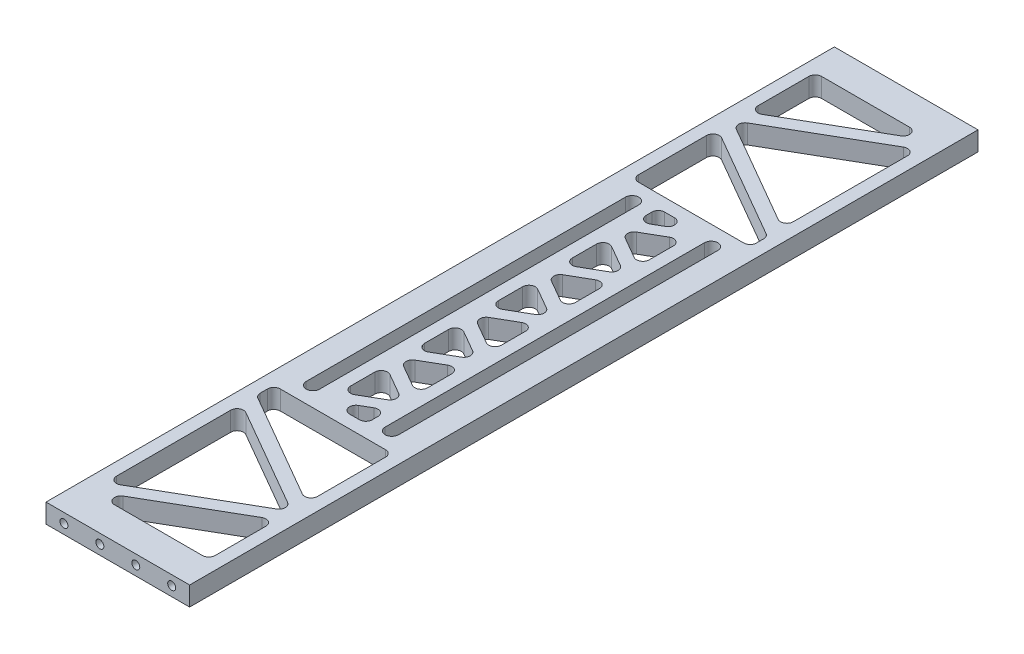
SolidWorks part; units mm, degrees
material "Сплав 2024"
ref_plane "Спереди" through (0, 0, 0) normal (0, 0, 1) x (1, 0, 0)
ref_plane "Сверху" through (0, 0, 0) normal (0, 1, 0) x (1, 0, 0)
ref_plane "Справа" through (0, 0, 0) normal (1, 0, 0) x (0, 0, -1)
sketch "Эскиз1" plane through (0, 0, 0) normal (0, 1, 0) x (1, 0, 0)
  line L2 (-15.9099, 15.9099) -> (15.9099, -15.9099) construction
  line L3 (15.9099, 15.9099) -> (-15.9099, -15.9099) construction
  line L4 (-22.5, 0) -> (-22.5, -247)
  line L5 (-22.5, -247) -> (22.5, -247)
  line L6 (22.5, 0) -> (22.5, -247)
  line L7 (-22.5, 0) -> (22.5, 0)
  dimension "D1" = 247
  dimension "D2" = 45
  dimension "D3" = 45
extrude "Бобышка-Вытянуть1" add sketch "Эскиз1" along normal blind 6
sketch "Эскиз2" plane through (0, 6, 0) normal (0, 1, 0) x (1, 0, 0)
  line L2 (0, 0) -> (0, -247) construction
  line L3 (-22.5, -247) -> (22.5, -247) construction
  line L4 (-12.3744, -135.8744) -> (12.3744, -111.1256) construction
  line L5 (-12.3744, -73.5) -> (-12.3744, -173.5) construction
  line L6 (-10.2744, -73.5) -> (-10.2744, -173.5)
  line L7 (-14.4744, -73.5) -> (-14.4744, -173.5)
  line L8 (-12.3744, -111.1256) -> (12.3744, -135.8744) construction
  line L9 (12.3744, -73.5) -> (12.3744, -173.5) construction
  line L10 (10.2744, -73.5) -> (10.2744, -173.5)
  line L11 (14.4744, -73.5) -> (14.4744, -173.5)
  line L13 (-22.5, -123.5) -> (22.5, -123.5) construction
  line L14 (-22.5, 0) -> (-22.5, -247) construction
  line L15 (22.5, -247) -> (22.5, 0) construction
  circle A0 centre (0, -123.5) radius 6 construction
  circle A1 centre (0, -123.5) radius 17.5 construction
  arc A2 (-10.2744, -73.5) -> (-14.4744, -73.5) centre (-12.3744, -73.5) ccw
  arc A3 (-14.4744, -173.5) -> (-10.2744, -173.5) centre (-12.3744, -173.5) ccw
  arc A4 (10.2744, -73.5) -> (14.4744, -73.5) centre (12.3744, -73.5) cw
  arc A5 (14.4744, -173.5) -> (10.2744, -173.5) centre (12.3744, -173.5) cw
  point P13 (12.3744, -123.5)
  point P18 (-12.3744, -123.5)
  point P37 (0, -123.5)
  dimension "D1" = 12
  dimension "D2" = 35
  dimension "D4" = 2.1
  dimension "D3" = 45
  dimension "D5" = 100
hole_wizard "Цековка для  винта с полукруглой головкой M31" [suppressed] positions "Эскиз4" profile "Эскиз5" counterbore size "M3" standard "Ansi Metric"
sketch "Эскиз4" plane through (0, 6, 0) normal (0, 1, 0) x (1, 0, 0)
  line L2 (-36.6046, 36.6046) -> (36.6046, -36.6046) construction
  line L3 (-12.3744, -12.3744) -> (12.3744, 12.3744) construction
  circle A0 centre (0, 0) radius 6 construction
  point P0 (-4.2426, 4.2426)
  point P6 (-4.2426, -4.2426)
  point P10 (4.2426, -4.2426)
  point P12 (4.2426, 4.2426)
sketch "Эскиз5" plane through (-4.2426, 6, -4.2426) normal (1, 0, 0) x (0, 0, 1)
  line L0 (0, 0) -> (0, 6)
  line L1 (0, 6) -> (1.7, 6)
  line L3 (1.7, 6) -> (1.7, 2)
  line L4 (1.7, 2) -> (3.35, 2)
  line L5 (3.35, 2) -> (3.35, 0)
  line L7 (3.35, 0) -> (0, 0)
  line L11 (0, -6.35) -> (0, 107.95) construction
  dimension "Диаметр сквозного отверстия" = 3.4
  dimension "Глубина сквозного отверстия" = 6
  dimension "Диаметр цековки" = 6.7
  dimension "Глубина цековки" = 2
hole_wizard "Отверстие обработанное метчиком M4x0.71" [suppressed] positions "Эскиз7" profile "Эскиз6" tap size "M4x0.7" standard "Ansi Metric"
sketch "Эскиз7" [suppressed] plane through (0, 4, 0) normal (0, 1, 0) x (1, 0, 0)
  line L0 (22.5, 0) -> (-22.5, 0) construction
  line L1 (0, 22.5) -> (0, -22.5) construction
  circle A0 centre (0, 0) radius 19.25 construction
  point P0 (-19.25, 0)
  point P6 (0, -19.25)
  point P10 (19.25, 0)
  point P12 (0, 19.25)
sketch "Эскиз6" plane through (-19.25, 4, 0) normal (1, 0, 0) x (0, 0, 1)
  line L0 (0, 0) -> (0, 4)
  line L1 (0, 4) -> (1.65, 4)
  line L2 (1.65, 4) -> (1.65, 0)
  line L5 (1.65, 0) -> (0, 0)
  line L11 (0, -6.35) -> (0, 107.95) construction
  dimension "Диаметр резьбы" = 3.3
  dimension "Глубина проходного сверла" = 4
extrude "Вырез-Вытянуть1" cut sketch "Эскиз2" against normal through all
sketch "Эскиз8" plane through (0, 0, 247) normal (0, 0, 1) x (1, 0, 0)
  line L0 (-22.5, 3) -> (22.5, 3) construction
  line L1 (-22.5, 6) -> (-22.5, 0) construction
  line L2 (22.5, 6) -> (22.5, 0) construction
  line L3 (-16.875, 6) -> (-16.875, 0) construction
  line L4 (-22.5, 6) -> (22.5, 6) construction
  line L5 (-22.5, 0) -> (22.5, 0) construction
  line L6 (-11.25, 6) -> (-11.25, 0) construction
  line L7 (-5.625, 6) -> (-5.625, 0) construction
  line L8 (0, 6) -> (0, 0) construction
  line L9 (5.625, 6) -> (5.625, 0) construction
  line L10 (11.25, 0) -> (11.25, 6) construction
  line L11 (16.875, 6) -> (16.875, 0) construction
  dimension "D1" = 45
  dimension "D2" = 5.625
  dimension "D3" = 5.625
  dimension "D4" = 5.625
  dimension "D5" = 5.625
  dimension "D6" = 5.625
  dimension "D7" = 5.625
  dimension "D8" = 5.625
sketch "Эскиз14" plane through (0, 6, 0) normal (0, 1, 0) x (1, 0, 0)
  line L0 (-22.5, -10) -> (22.5, -10) construction
  line L1 (-22.5, 0) -> (-22.5, -247) construction
  line L2 (22.5, -247) -> (22.5, 0) construction
  line L3 (-22.5, -237) -> (22.5, -237) construction
  line L4 (-22.5, -247) -> (22.5, -247) construction
  line L5 (22.5, 0) -> (-22.5, 0) construction
  line L6 (-18.5, 0) -> (-18.5, -247) construction
  line L7 (18.5, -247) -> (18.5, 0) construction
  line L8 (-22.5, -123.5) -> (22.5, -123.5) construction
  line L9 (-18.5, -10) -> (18.5, -10)
  line L10 (18.5, -10) -> (-18.5, -31.362)
  line L11 (-18.5, -31.362) -> (-18.5, -10)
  line L12 (-18.5, -35.9808) -> (18.5, -14.6188)
  line L13 (18.5, -14.6188) -> (18.5, -57.3427)
  line L14 (-18.5, -35.9808) -> (18.5, -57.3427)
  line L15 (-18.5, -40.5996) -> (-18.5, -67.4)
  line L16 (-6.2744, 0) -> (-6.2744, -247) construction
  line L17 (6.2744, -247) -> (6.2744, 0) construction
  line L19 (-10.2744, -173.5) -> (-10.2744, -73.5) construction
  line L20 (10.2744, -73.5) -> (10.2744, -173.5) construction
  line L21 (-22.5, -71.4) -> (22.5, -71.4) construction
  line L22 (-22.5, -175.6) -> (22.5, -175.6) construction
  line L23 (6.2744, -71.4) -> (-6.2744, -78.645)
  line L24 (6.2744, -75.7301) -> (-6.2744, -82.9751)
  line L25 (-6.2744, -82.9751) -> (6.2744, -90.2202)
  line L26 (6.2744, -90.2202) -> (6.2744, -75.7301)
  line L27 (-6.2744, -78.645) -> (-6.2744, -71.4)
  line L28 (-6.2744, -71.4) -> (6.2744, -71.4)
  line L29 (-6.2744, -87.3053) -> (6.2744, -94.5503)
  line L30 (6.2744, -94.5503) -> (-6.2744, -101.7953)
  line L31 (-6.2744, -101.7953) -> (-6.2744, -87.3053)
  line L32 (-6.2744, -106.1254) -> (6.2744, -98.8804)
  line L33 (6.2744, -98.8804) -> (6.2744, -113.3704)
  line L34 (6.2744, -113.3704) -> (-6.2744, -106.1254)
  line L35 (-6.2744, -110.4556) -> (6.2744, -117.7006)
  line L36 (6.2744, -117.7006) -> (-6.2744, -124.9456)
  line L37 (-6.2744, -124.9456) -> (-6.2744, -110.4556)
  line L38 (-6.2744, -129.2757) -> (6.2744, -122.0307)
  line L39 (6.2744, -122.0307) -> (6.2744, -136.5207)
  line L40 (6.2744, -136.5207) -> (-6.2744, -129.2757)
  line L41 (-6.2744, -133.6058) -> (6.2744, -140.8509)
  line L42 (6.2744, -140.8509) -> (-6.2744, -148.0959)
  line L43 (-6.2744, -148.0959) -> (-6.2744, -133.6058)
  line L44 (-6.2744, -152.426) -> (6.2744, -145.181)
  line L45 (6.2744, -145.181) -> (6.2744, -159.671)
  line L46 (6.2744, -159.671) -> (-6.2744, -152.426)
  line L47 (-6.2744, -156.7561) -> (6.2744, -164.0012)
  line L48 (6.2744, -164.0012) -> (-6.2744, -171.2462)
  line L49 (-6.2744, -171.2462) -> (-6.2744, -156.7561)
  line L50 (-6.2744, -175.5763) -> (6.2744, -168.3313)
  line L51 (6.2744, -168.3313) -> (6.2744, -175.5763)
  line L52 (6.2744, -175.5763) -> (-6.2744, -175.5763)
  line L53 (-18.5, -67.4) -> (18.5, -67.4)
  line L54 (18.5, -67.4) -> (18.5, -61.9615)
  line L55 (18.5, -61.9615) -> (-18.5, -40.5996)
  line L65 (0, -247) -> (0, -241.1177) construction
  line L67 (-18.5, -179.6) -> (-18.5, -185.0385)
  line L68 (-18.5, -232.3812) -> (-18.5, -189.6573)
  line L69 (18.5, -215.638) -> (18.5, -237)
  line L70 (18.5, -237) -> (-18.5, -237)
  line L71 (-18.5, -237) -> (18.5, -215.638)
  line L72 (18.5, -211.0192) -> (-18.5, -232.3812)
  line L73 (18.5, -211.0192) -> (-18.5, -189.6573)
  line L74 (-18.5, -185.0385) -> (18.5, -206.4004)
  line L75 (18.5, -206.4004) -> (18.5, -179.6)
  line L76 (18.5, -179.6) -> (-18.5, -179.6)
  arc A0 (-10.2744, -73.5) -> (-14.4744, -73.5) centre (-12.3744, -73.5) ccw construction
  arc A1 (10.2744, -173.5) -> (14.4744, -173.5) centre (12.3744, -173.5) ccw construction
  dimension "D1" = 10
  dimension "D2" = 10
  dimension "D3" = 4
  dimension "D4" = 4
  dimension "D5" = 4
  dimension "D6" = 4
  dimension "D7" = 30
  dimension "D8" = 3.75
  dimension "D9" = 60
  dimension "D10" = 3.75
  dimension "D11" = 60
  dimension "D12" = 3.75
  dimension "D13" = 60
  dimension "D14" = 3.75
  dimension "D15" = 60
  dimension "D16" = 3.75
  dimension "D17" = 3.75
  dimension "D18" = 3.75
  dimension "D19" = 3.75
  dimension "D20" = 60
  dimension "D21" = 60
  dimension "D22" = 60
  dimension "D23" = 60
  dimension "D24" = 3.75
  dimension "D25" = 30
  dimension "D26" = 4
  dimension "D27" = 60
  dimension "D28" = 4
  dimension "D29" = 4
  dimension "D30" = 4
  dimension "D31" = 4
  dimension "D32" = 4
  dimension "D33" = 30
  dimension "D34" = 60
extrude "Вырез-Вытянуть2" cut sketch "Эскиз14" against normal through all
fillet "Скругление1" radius 2 50 edges at (-6.2744, 3, 175.5763) (6.2744, 3, 175.5763) (6.2744, 3, 168.3313) (6.2744, 3, 145.181) (-6.2744, 3, 152.426) (-6.2744, 3, 156.7561) (6.2744, 3, 164.0012) (6.2744, 3, 159.671) (-6.2744, 3, 171.2462) (-6.2744, 3, 148.0959) (6.2744, 3, 140.8509) (-6.2744, 3, 133.6058) (6.2744, 3, 122.0307) (6.2744, 3, 136.5207) (-6.2744, 3, 129.2757) (6.2744, 3, 117.7006) (-6.2744, 3, 110.4556) (-6.2744, 3, 124.9456) (-6.2744, 3, 101.7953) (6.2744, 3, 94.5503) (-6.2744, 3, 106.1254) (6.2744, 3, 113.3704) (6.2744, 3, 98.8804) (-6.2744, 3, 87.3053) (6.2744, 3, 90.2202) (6.2744, 3, 75.7301) (-6.2744, 3, 82.9751) (-6.2744, 3, 78.645) (-6.2744, 3, 71.4) (6.2744, 3, 71.4) (-18.5, 3, 40.5996) (-18.5, 3, 67.4) (18.5, 3, 67.4) (18.5, 3, 61.9615) (18.5, 3, 57.3427) (18.5, 3, 14.6188) (-18.5, 3, 35.9808) (-18.5, 3, 31.362) (18.5, 3, 10) (-18.5, 3, 10) (18.5, 3, 237) (18.5, 3, 215.638) (-18.5, 3, 237) (-18.5, 3, 232.3812) (18.5, 3, 211.0192) (-18.5, 3, 189.6573) (18.5, 3, 206.4004) (-18.5, 3, 185.0385) (-18.5, 3, 179.6) (18.5, 3, 179.6)
chamfer "Фаска1" [suppressed] distance 1 angle 45
hole_wizard "Отверстие обработанное метчиком M3x0.52" positions "Эскиз12" profile "Эскиз11" tap size "M3x0.5" standard "Ansi Metric"
sketch "Эскиз12" plane through (0, 0, 0) normal (0, 0, -1) x (-1, 0, 0)
  line L3 (16.875, 6) -> (16.875, 0) construction
  line L4 (-16.875, 6) -> (-16.875, 0) construction
  line L5 (-5.625, 6) -> (-5.625, 0) construction
  line L6 (5.625, 6) -> (5.625, 0) construction
  point P0 (-16.875, 3)
  point P4 (-5.625, 3)
  point P8 (5.625, 3)
  point P12 (16.875, 3)
sketch "Эскиз11" plane through (16.875, 3, 0) normal (1, 0, 0) x (0, 1, 0)
  line L0 (0, 0) -> (0, 9.2511)
  line L1 (0, 9.2511) -> (1.25, 8.5)
  line L2 (1.25, 8.5) -> (1.25, 0)
  line L5 (1.25, 0) -> (0, 0)
  line L10 (0, 9.2511) -> (-1.25, 8.5) construction
  line L11 (0, -6.35) -> (0, 107.95) construction
  dimension "Диаметр сверла" = 2.5
  dimension "Глубина сверла" = 8.5
  dimension "Угол заточки сверла" = 118
cosmetic thread "Отверстие резьбы5" parameters "D1"=6, "D2"=3
cosmetic thread "Отверстие резьбы6" parameters "D1"=6, "D2"=3
cosmetic thread "Отверстие резьбы7" parameters "D1"=6, "D2"=3
cosmetic thread "Отверстие резьбы8" parameters "D1"=6, "D2"=3
hole_wizard "Отверстие обработанное метчиком M3x0.51" positions "Эскиз10" profile "Эскиз9" tap size "M3x0.5" standard "Ansi Metric"
sketch "Эскиз10" plane through (0, 0, 247) normal (0, 0, 1) x (1, 0, 0)
  line L0 (-16.875, 6) -> (-16.875, 0) construction
  line L4 (16.875, 6) -> (16.875, 0) construction
  line L5 (5.625, 6) -> (5.625, 0) construction
  line L6 (-5.625, 6) -> (-5.625, 0) construction
  point P0 (-16.875, 3)
  point P4 (-5.625, 3)
  point P8 (5.625, 3)
  point P12 (16.875, 3)
sketch "Эскиз9" plane through (-16.875, 3, 247) normal (1, 0, 0) x (0, -1, 0)
  line L0 (0, 0) -> (0, 9.2511)
  line L1 (0, 9.2511) -> (1.25, 8.5)
  line L2 (1.25, 8.5) -> (1.25, 0)
  line L5 (1.25, 0) -> (0, 0)
  line L10 (0, 9.2511) -> (-1.25, 8.5) construction
  line L11 (0, -6.35) -> (0, 107.95) construction
  dimension "Диаметр сверла" = 2.5
  dimension "Глубина сверла" = 8.5
  dimension "Угол заточки сверла" = 118
cosmetic thread "Отверстие резьбы1" parameters "D1"=6, "D2"=3
cosmetic thread "Отверстие резьбы2" parameters "D1"=6, "D2"=3
cosmetic thread "Отверстие резьбы3" parameters "D1"=6, "D2"=3
cosmetic thread "Отверстие резьбы4" parameters "D1"=6, "D2"=3
equation "\"D2@Эскиз8\"=\"D1@Эскиз8\"/8"
equation "\"D3@Эскиз8\"=\"D2@Эскиз8\""
equation "\"D4@Эскиз8\"=\"D2@Эскиз8\""
equation "\"D5@Эскиз8\"=\"D2@Эскиз8\""
equation "\"D10@Эскиз14\"=\"D8@Эскиз14\""
equation "\"D12@Эскиз14\"=\"D8@Эскиз14\""
equation "\"D14@Эскиз14\"=\"D8@Эскиз14\""
equation "\"D16@Эскиз14\"=\"D8@Эскиз14\""
equation "\"D17@Эскиз14\"=\"D16@Эскиз14\""
equation "\"D18@Эскиз14\"=\"D16@Эскиз14\""
equation "\"D19@Эскиз14\"=\"D18@Эскиз14\""
equation "\"D9@Эскиз14\"=\"D7@Эскиз14\"*2"
equation "\"D11@Эскиз14\"=\"D9@Эскиз14\""
equation "\"D13@Эскиз14\"=\"D9@Эскиз14\""
equation "\"D15@Эскиз14\"=\"D9@Эскиз14\""
equation "\"D20@Эскиз14\"=\"D15@Эскиз14\""
equation "\"D21@Эскиз14\"=\"D15@Эскиз14\""
equation "\"D22@Эскиз14\"=\"D15@Эскиз14\""
equation "\"D23@Эскиз14\"=\"D15@Эскиз14\""
equation "\"D24@Эскиз14\"=\"D19@Эскиз14\""
equation "\"D27@Эскиз14\"=\"D25@Эскиз14\"*2"
equation "\"D33@Эскиз14\"=\"D25@Эскиз14\""
equation "\"D34@Эскиз14\"=\"D33@Эскиз14\"*2"
equation "\"D6@Эскиз8\"=\"D2@Эскиз8\""
equation "\"D7@Эскиз8\"=\"D2@Эскиз8\""
equation "\"D8@Эскиз8\"=\"D2@Эскиз8\""
